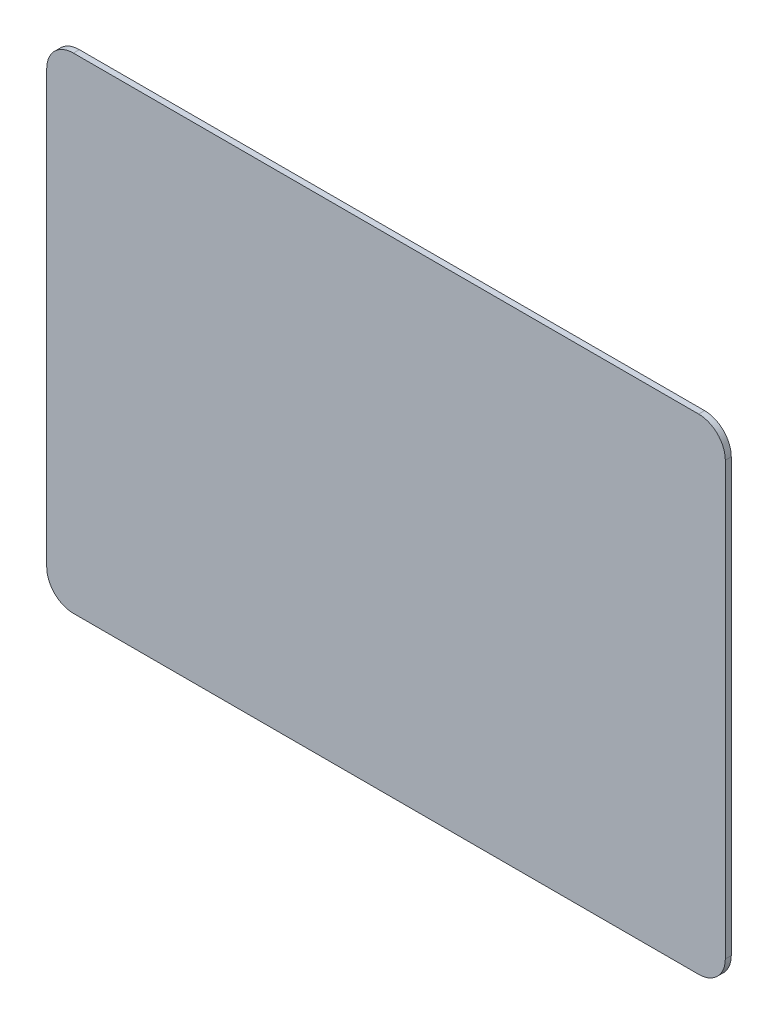
SolidWorks part; units mm, degrees
ref_plane "Front Plane" through (0, 0, 0) normal (0, 0, 1) x (1, 0, 0)
ref_plane "Top Plane" through (0, 0, 0) normal (0, 1, 0) x (1, 0, 0)
ref_plane "Right Plane" through (0, 0, 0) normal (1, 0, 0) x (0, 0, -1)
sketch "Sketch1" plane through (0, 0, 0) normal (0, 0, 1) x (1, 0, 0)
  line L1 (-41.4059, 47.4562) -> (292.0961, 47.4562)
  line L2 (-55.6299, 33.2322) -> (-55.6299, -197.1458)
  line L3 (-41.4059, -211.3698) -> (292.0961, -211.3698)
  line L4 (306.3201, 33.2322) -> (306.3201, -197.1458)
  arc A0 (-41.4059, 47.4562) -> (-55.6299, 33.2322) centre (-41.4059, 33.2322) ccw
  arc A1 (-55.6299, -197.1458) -> (-41.4059, -211.3698) centre (-41.4059, -197.1458) ccw
  arc A2 (292.0961, -211.3698) -> (306.3201, -197.1458) centre (292.0961, -197.1458) ccw
  arc A3 (306.3201, 33.2322) -> (292.0961, 47.4562) centre (292.0961, 33.2322) ccw
  point P6 (-55.6299, 47.4562)
  point P9 (-55.6299, -211.3698)
  point P14 (306.3201, 47.4562)
  dimension "D3" = 14.224
  dimension "D4" = 14.224
  dimension "D1" = 361.95
  dimension "D2" = 258.826
extrude "Boss-Extrude1" add sketch "Sketch1" against normal blind 3.175
